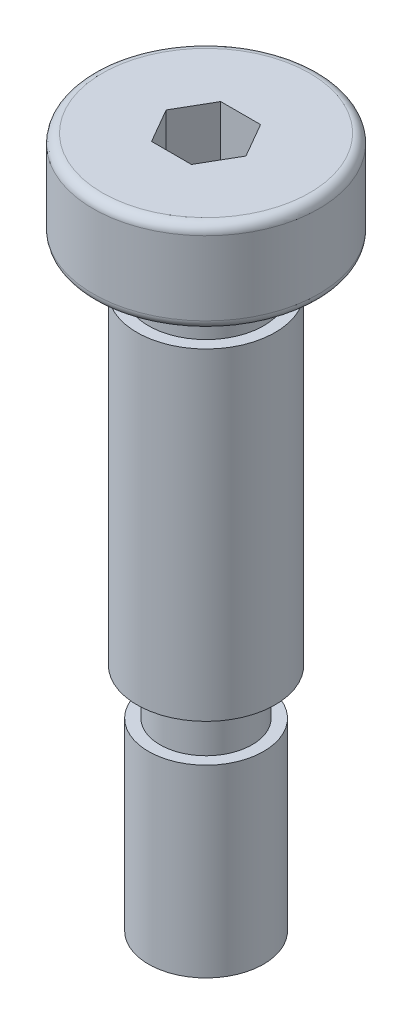
SolidWorks part; units mm, degrees
material "AISI 304"
ref_plane "前视基准面" through (0, 0, 0) normal (0, 0, 1) x (1, 0, 0)
ref_plane "上视基准面" through (0, 0, 0) normal (0, 1, 0) x (1, 0, 0)
ref_plane "右视基准面" through (0, 0, 0) normal (1, 0, 0) x (0, 0, -1)
sketch "草图1" plane through (0, 0, 0) normal (0, 0, 1) x (1, 0, 0)
  line L0 (0, 0) -> (0, 30) construction
  line L1 (0, 30) -> (-4.5, 30)
  line L2 (-4.9, 29.6) -> (-4.9, 26.4)
  line L3 (-4.5, 26) -> (-2.5, 26)
  line L4 (-2.5, 26) -> (-2.5, 24)
  line L5 (-2.5, 24) -> (-3, 24)
  line L6 (-3, 24) -> (-3, 10)
  line L7 (-3, 10) -> (-2, 10)
  line L8 (-2, 10) -> (-2, 8)
  line L9 (-2, 8) -> (-2.5, 8)
  line L10 (-2.5, 8) -> (-2.5, 0)
  line L11 (-2.5, 0) -> (0, 0)
  line L12 (0, 0) -> (0, 30)
  arc A0 (-4.9, 26.4) -> (-4.5, 26) centre (-4.5, 26.4) ccw
  arc A1 (-4.5, 30) -> (-4.9, 29.6) centre (-4.5, 29.6) ccw
  point P17 (-4.9, 26)
  point P20 (-4.9, 30)
  dimension "D11" = 0.4
  dimension "D1" = 4
  dimension "D2" = 9.8
  dimension "D3" = 6
  dimension "D4" = 2
  dimension "D5" = 0.5
  dimension "D6" = 10
  dimension "D7" = 5
  dimension "D8" = 4
  dimension "D9" = 2
  dimension "D10" = 16
revolve "旋转1" add sketch "草图1" angle 360 about L0
cosmetic thread "装饰螺纹线1" parameters "D2"=4.11
sketch "草图2" plane through (0, 30, 0) normal (0, 1, 0) x (1, 0, 0)
  line L1 (0.866, 1.5) -> (-0.866, 1.5)
  line L2 (-0.866, 1.5) -> (-1.7321, 0)
  line L3 (-1.7321, 0) -> (-0.866, -1.5)
  line L4 (-0.866, -1.5) -> (0.866, -1.5)
  line L5 (0.866, -1.5) -> (1.7321, 0)
  line L6 (1.7321, 0) -> (0.866, 1.5)
  circle A0 centre (0, 0) radius 1.5 construction
  dimension "D1" = 3
extrude "切除-拉伸1" cut sketch "草图2" against normal blind 3.5
